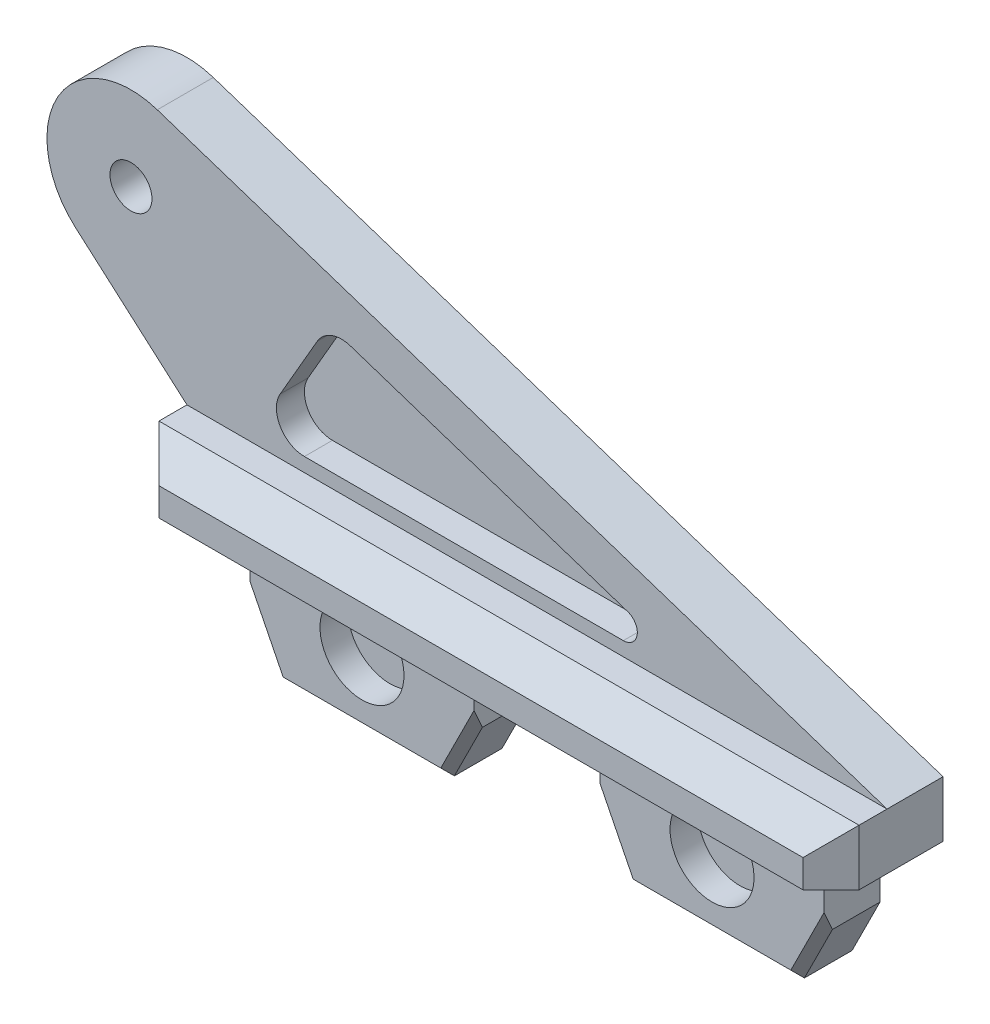
SolidWorks part; units mm, degrees
ref_plane "Ebene vorne" through (0, 0, 0) normal (0, 0, 1) x (1, 0, 0)
ref_plane "Ebene oben" through (0, 0, 0) normal (0, 1, 0) x (1, 0, 0)
ref_plane "Ebene rechts" through (0, 0, 0) normal (1, 0, 0) x (0, 0, -1)
sketch "Skizze1" plane through (0, 0, 0) normal (0, 0, 1) x (1, 0, 0)
  line L0 (0, 0) -> (-2, 7.746) construction
  line L1 (0, 0) -> (6.25, 0) construction
  line L2 (12.5, 0) -> (12.5, -4.6364) construction
  line L3 (6.25, 0) -> (6.25, -5) construction
  line L4 (9.25, -5) -> (3.25, -5)
  line L5 (0, 0) -> (2.25, 0)
  line L6 (2.25, 0) -> (2.25, -3)
  line L7 (2.25, -3) -> (3.25, -5)
  line L8 (10.25, -3) -> (9.25, -5)
  line L9 (10.25, 0) -> (10.25, -3)
  line L10 (14.75, 0) -> (10.25, 0)
  line L11 (18.75, 0) -> (18.75, -5) construction
  line L12 (14.75, 0) -> (14.75, -3)
  line L13 (14.75, -3) -> (15.75, -5)
  line L14 (15.75, -5) -> (21.75, -5)
  line L15 (22.75, -3) -> (21.75, -5)
  line L16 (22.75, 0) -> (22.75, -3)
  line L17 (25, 0) -> (22.75, 0)
  line L18 (25, 0) -> (25, 2)
  line L19 (25, 2) -> (-1.0604, 10.595)
  line L20 (-3.9786, 5.491) -> (0, 2)
  line L21 (0, 2) -> (0, 0)
  circle A0 centre (-2, 7.746) radius 0.75
  arc A2 (-1.0604, 10.595) -> (-3.9786, 5.491) centre (-2, 7.746) ccw
  point P28 (0, 0)
  dimension "D1" = 1.5
  dimension "D12" = 3
  dimension "D3" = 8
  dimension "D4" = 8
  dimension "D5" = 25
  dimension "D6" = 4.5
  dimension "D7" = 2
  dimension "D8" = 2
  dimension "D9" = 5
  dimension "D10" = 3
  dimension "D11" = 6
extrude "Aufsatz-Linear austragen1" add sketch "Skizze1" along normal blind 2
sketch "Skizze2" plane through (0, 0, 2) normal (0, 0, 1) x (1, 0, 0)
  line L0 (12.5, 0) -> (12.5, -4.8963) construction
  line L1 (10.25, 0) -> (14.75, 0) construction
  line L2 (2.25, 0) -> (6.25, 0) construction
  line L3 (6.25, 0) -> (10.25, 0) construction
  line L4 (6.25, 0) -> (6.25, -2.5) construction
  line L5 (6.25, -2.5) -> (6.25, -5) construction
  line L6 (3.25, -5) -> (9.25, -5) construction
  line L7 (18.75, -2.5) -> (18.75, -5) construction
  line L8 (18.75, 0) -> (18.75, -2.5) construction
  line L9 (18.75, 0) -> (14.75, 0) construction
  line L10 (22.75, 0) -> (18.75, 0) construction
  circle A0 centre (6.25, -2.5) radius 1.5
  circle A1 centre (18.75, -2.5) radius 1.5
  dimension "D1" = 3
extrude "Schnitt-Linear austragen1" cut sketch "Skizze2" against normal blind 1
sketch "Skizze3" plane through (0, 0, 2) normal (0, 0, 1) x (1, 0, 0)
  line L1 (0, 2) -> (25, 2)
  line L2 (0, 2) -> (0, 0)
  line L3 (0, 0) -> (25, 0)
  line L4 (25, 2) -> (25, 0)
extrude "Aufsatz-Linear austragen2" add sketch "Skizze3" along normal blind 2
chamfer "Fase1" distance 1 angle 45 3 edges at (25, 1, 4) (12.5, 2, 4) (0, 1, 4)
sketch "Skizze4" plane through (0, 0, 2) normal (0, 0, 1) x (1, 0, 0)
  line L0 (5.0591, 6.9973) -> (18.695, 2.5)
  line L1 (18.695, 2.5) -> (2.4626, 2.5)
  line L2 (2.4626, 2.5) -> (5.0591, 6.9973)
  line L3 (25, 2) -> (0, 2) construction
  line L4 (25, 2) -> (-1.0604, 10.595) construction
  line L5 (0, 2) -> (25, 2) construction
  line L6 (-3.9786, 5.491) -> (0, 2) construction
  point P11 (1.3096, 8.2339)
  dimension "D1" = 1.5
  dimension "D2" = 0.5
  dimension "D3" = 2
  dimension "D4" = 60
extrude "Schnitt-Linear austragen2" cut sketch "Skizze4" against normal blind 1
fillet "Verrundung1" radius 1 2 edges at (2.4626, 2.5, 1.5) (5.0591, 6.9973, 1.5)
fillet "Verrundung2" radius 0.5 1 edges at (18.695, 2.5, 1.5)
chamfer "Fase2" distance 0.3 angle 45 6 edges at (22.25, -4, 2) (18.75, -5, 2) (15.25, -4, 2) (9.75, -4, 2) (6.25, -5, 2) (2.75, -4, 2)
